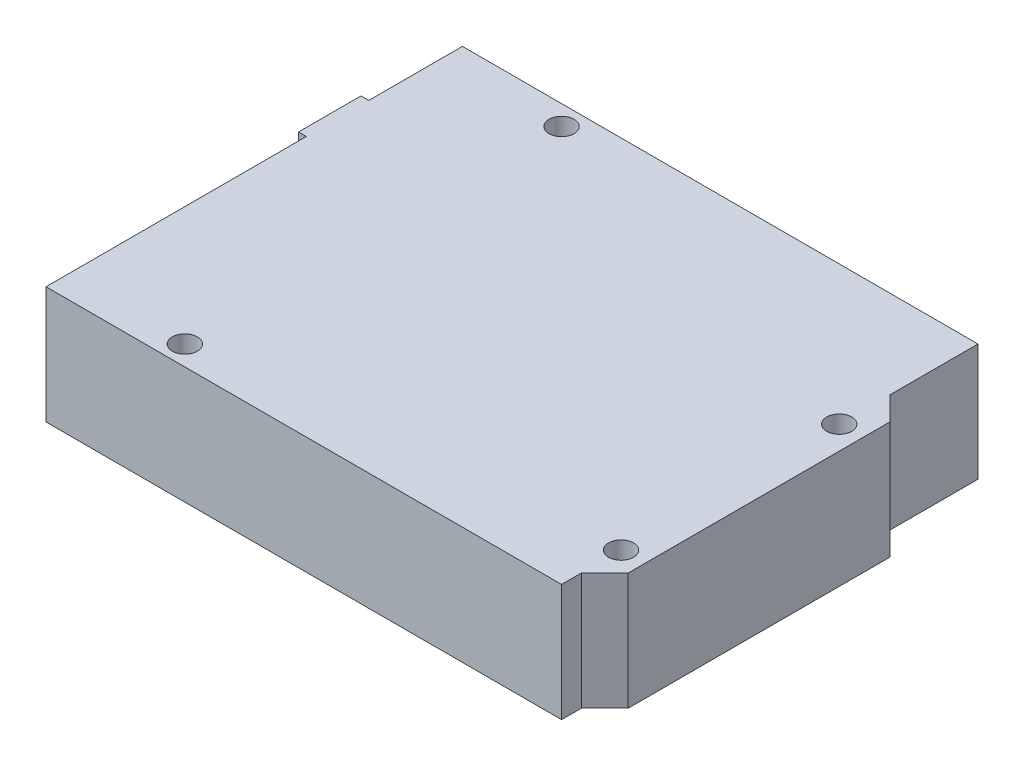
SolidWorks part; units mm, degrees
ref_plane "Płaszczyzna przednia" through (0, 0, 0) normal (0, 0, 1) x (1, 0, 0)
ref_plane "Płaszczyzna górna" through (0, 0, 0) normal (0, 1, 0) x (1, 0, 0)
ref_plane "Płaszczyzna prawa" through (0, 0, 0) normal (1, 0, 0) x (0, 0, -1)
sketch "Szkic1" plane through (0, 0, 0) normal (0, 1, 0) x (1, 0, 0)
  line L12 (0, -2.54) -> (66.04, -2.54)
  line L14 (66.04, 50.8) -> (0, 50.8)
  line L15 (66.04, 50.8) -> (66.04, 39.5)
  line L16 (0, 50.8) -> (0, 38.8)
  line L17 (66.04, -2.54) -> (66.04, 0)
  line L18 (69.04, 3) -> (69.04, 36.5)
  line L19 (69.04, 36.5) -> (66.04, 39.5)
  line L21 (66.04, 0) -> (69.04, 3)
  line L22 (0, 38.8) -> (-1, 38.8)
  line L23 (-1, 38.8) -> (-1, 30.8)
  line L24 (-1, 30.8) -> (0, 30.8)
  line L26 (0, 30.8) -> (0, 9)
  line L27 (0, 9) -> (-2, 9)
  line L28 (-2, 9) -> (-2, 0)
  line L29 (-2, 0) -> (0, 0)
  line L31 (0, 0) -> (0, -2.54)
  circle A0 centre (15.24, 0) radius 1.6
  circle A1 centre (66.04, 33.02) radius 1.6
  circle A2 centre (66.04, 5.08) radius 1.6
  circle A3 centre (15.24, 48.26) radius 1.6
extrude "Dodanie-wyciągnięcie1" add sketch "Szkic1" along normal blind 15
sketch "Szkic2" plane through (0, 15, 0) normal (0, 1, 0) x (1, 0, 0)
  line L0 (0, 9) -> (-2, 9)
  line L1 (-2, 9) -> (-2, 0)
  line L2 (-2, 0) -> (0, 0)
  line L3 (0, 0) -> (0, 9)
extrude "Wytnij-wyciągnięcie1" cut sketch "Szkic2" against normal through all
